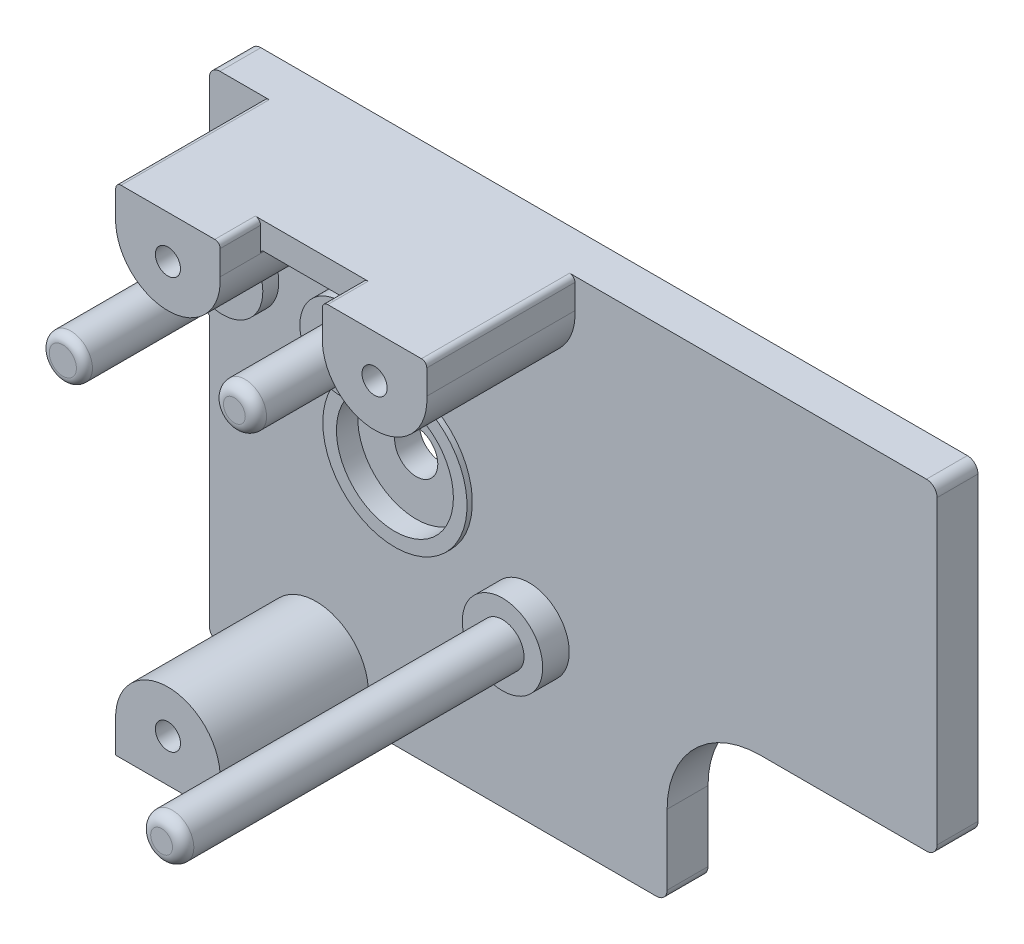
SolidWorks part; units mm, degrees
ref_plane "Alzado" through (0, 0, 0) normal (0, 0, 1) x (1, 0, 0)
ref_plane "Planta" through (0, 0, 0) normal (0, 1, 0) x (1, 0, 0)
ref_plane "Vista lateral" through (0, 0, 0) normal (1, 0, 0) x (0, 0, -1)
sketch "Croquis1" plane through (0, 0, 0) normal (0, 0, 1) x (1, 0, 0)
  line L0 (0, -55) -> (0, 55) construction
  line L1 (-68.325, 28.78) -> (68.325, 28.78)
  line L2 (-68.325, 28.78) -> (-68.325, 11.9)
  line L3 (-68.325, -64.4) -> (17.635, -64.4)
  line L4 (68.325, 28.78) -> (68.325, -31.7)
  line L5 (55, 0) -> (-55, 0) construction
  line L6 (17.635, -64.4) -> (17.635, -49.23)
  line L7 (35.165, -31.7) -> (68.325, -31.7)
  line L8 (-68.325, 0) -> (-104.5654, 0) construction
  line L9 (-73.325, 7.775) -> (-73.325, -7.775)
  line L10 (-73.325, 7.775) -> (-68.325, 11.9)
  line L11 (-73.325, -7.775) -> (-68.325, -11.9)
  line L12 (-68.325, -11.9) -> (-68.325, -64.4)
  arc A0 (17.635, -49.23) -> (35.165, -31.7) centre (35.165, -49.23) cw
  point P1 (-68.325, 11.9)
  point P4 (0, 28.78)
  point P5 (-68.325, 0)
  point P10 (17.635, -64.4)
  point P11 (68.325, -31.7)
  point P14 (34.845, -31.7)
  point P16 (17.635, -51.65)
  point P19 (-68.325, -11.9)
  point P23 (-73.325, 0)
  point P25 (-73.325, 0)
  dimension "D7" = 17.53
  dimension "D1" = 93.18
  dimension "D2" = 15.55
  dimension "D3" = 60.48
  dimension "D4" = 85.96
  dimension "D5" = 33.48
  dimension "D6" = 12.75
  dimension "D8" = 5
  dimension "D9" = 11.9
  dimension "D10" = 11.9
  dimension "D11" = 28.78
extrude "Saliente-Extruir1" add sketch "Croquis1" along normal mid plane 7.68
sketch "Croquis2" plane through (0, 0, 3.84) normal (0, 0, 1) x (1, 0, 0)
  line L0 (68.325, 28.78) -> (-68.325, 28.78) construction
  line L1 (-58.075, 28.78) -> (-58.075, 12.78) construction
  line L2 (-58.075, 12.78) -> (0.325, 12.78) construction
  line L3 (0.325, 12.78) -> (0.325, 28.78) construction
  line L4 (-58.075, 23.18) -> (0.325, 23.18) construction
  line L5 (-58.075, 23.18) -> (-58.075, 28.78)
  line L6 (-19.275, 28.78) -> (-19.275, 12.78) construction
  line L7 (-38.475, 28.78) -> (-38.475, 12.78) construction
  line L8 (-58.075, 28.78) -> (-38.475, 28.78)
  line L9 (-38.475, 28.78) -> (-38.475, 23.18)
  line L11 (-19.275, 23.18) -> (-19.275, 28.78)
  line L12 (-19.275, 28.78) -> (0.325, 28.78)
  line L13 (0.325, 28.78) -> (0.325, 23.18)
  arc A0 (-58.075, 23.18) -> (-38.475, 23.18) centre (-48.275, 22.5973) ccw
  arc A1 (-19.275, 23.18) -> (0.325, 23.18) centre (-9.475, 22.5973) ccw
  point P0 (0.325, 28.78)
  point P1 (-19.275, 28.78)
  point P5 (-38.475, 28.78)
  point P6 (-58.075, 28.78)
  point P15 (-38.475, 23.18)
  point P18 (-19.275, 23.18)
  point P19 (-58.075, 23.18)
  point P27 (-19.275, 23.18)
  dimension "D1" = 68
  dimension "D2" = 19.6
  dimension "D3" = 19.2
  dimension "D4" = 19.6
  dimension "D5" = 16
  dimension "D6" = 5.6
extrude "Saliente-Extruir2" add sketch "Croquis2" along normal blind 27.82
sketch "Croquis5" plane through (0, 0, 3.84) normal (0, 0, 1) x (1, 0, 0)
  line L0 (-38.475, 28.78) -> (-19.275, 28.78)
  line L1 (-19.275, 28.78) -> (-19.275, 23.82)
  line L2 (-19.275, 28.78) -> (-19.275, 23.18) construction
  line L3 (-19.275, 23.82) -> (-38.475, 23.82)
  line L4 (-38.475, 23.18) -> (-38.475, 28.78) construction
  line L5 (-38.475, 23.82) -> (-38.475, 28.78)
  dimension "D1" = 4.96
extrude "Saliente-Extruir3" add sketch "Croquis5" along normal blind 20.22
fillet "Redondeo1" radius 0.6 1 edges at (-38.475, 23.82, 13.95)
fillet "Redondeo4" radius 0.6 1 edges at (-19.275, 23.82, 13.95)
sketch "Croquis6" plane through (0, 0, 0) normal (0, 0, 1) x (1, 0, 0)
  line L0 (-38.475, 28.78) -> (-58.075, 28.78) construction
  line L1 (0.325, 28.78) -> (-19.275, 28.78) construction
  line L2 (-48.275, 28.78) -> (-48.275, 12.78) construction
  line L3 (-9.475, 28.78) -> (-9.475, 12.78) construction
  arc A0 (-58.075, 23.18) -> (-38.475, 23.18) centre (-48.275, 22.5973) ccw construction
  arc A1 (-19.275, 23.18) -> (0.325, 23.18) centre (-9.475, 22.5973) ccw construction
  circle A2 centre (-48.275, 20.78) radius 2.36
  circle A3 centre (-9.475, 20.78) radius 2.36
  point P0 (-48.275, 28.78)
  point P1 (-9.475, 28.78)
  point P16 (-48.275, 20.78)
  point P17 (-9.475, 20.78)
  dimension "D1" = 4.72
extrude "Cortar-Extruir1" cut sketch "Croquis6" against normal mid plane 107.9
sketch "Croquis9" plane through (0, 0, 3.84) normal (0, 0, 1) x (1, 0, 0)
  line L0 (-68.325, -64.4) -> (17.635, -64.4) construction
  line L2 (-58.075, -64.4) -> (-58.075, -48.4) construction
  line L3 (-58.075, -48.4) -> (-38.475, -48.4) construction
  line L4 (-38.475, -48.4) -> (-38.475, -64.4) construction
  line L5 (-58.075, -58.8) -> (-38.475, -58.8) construction
  line L6 (-58.075, -58.8) -> (-58.075, -64.4)
  line L7 (-58.075, -64.4) -> (-38.475, -64.4)
  line L8 (-38.475, -64.4) -> (-38.475, -58.8)
  line L9 (-58.075, 28.78) -> (-58.075, -64.4) construction
  arc A0 (-58.075, -58.8) -> (-38.475, -58.8) centre (-48.275, -58.2173) cw
  point P0 (-38.475, -64.4)
  point P5 (-58.075, -64.4)
  point P8 (-58.075, -58.8)
  dimension "D2" = 19.6
  dimension "D3" = 16
  dimension "D4" = 5.6
extrude "Saliente-Extruir6" add sketch "Croquis9" along normal blind 27.82
sketch "Croquis10" plane through (0, 0, 3.84) normal (0, 0, 1) x (1, 0, 0)
  line L0 (-58.075, 28.78) -> (-58.075, -64.4) construction
  line L1 (-58.075, -64.4) -> (-38.475, -64.4) construction
  line L2 (-48.275, -64.4) -> (-48.275, -48.4) construction
  arc A0 (-38.475, -58.8) -> (-58.075, -58.8) centre (-48.275, -58.2173) ccw construction
  circle A1 centre (-48.275, -56.4) radius 2.36
  point P5 (-48.275, -64.4)
  dimension "D1" = 4.72
extrude "Cortar-Extruir9" cut sketch "Croquis10" along normal blind 53 and the other way blind 66
fillet "Redondeo5" radius 5 1 edges at (-73.325, -7.775, 0)
fillet "Redondeo6" radius 5 1 edges at (-73.325, 7.775, 0)
sketch "Croquis12" plane through (0, 0, 3.84) normal (0, 0, 1) x (1, 0, 0)
  line L0 (-73.325, 5.4181) -> (-73.325, -5.4181) construction
  line L1 (19.525, 0) -> (-19.525, 0) construction
  line L2 (-62.825, 0) -> (-27.8016, 0) construction
  circle A0 centre (-62.825, 0) radius 4.05
  circle A1 centre (-38.625, 0) radius 4.05
  point P0 (-73.325, 0)
  point P1 (-62.825, 0)
  point P8 (-38.625, 0)
  dimension "D2" = 8.1
  dimension "D4" = 8.1
  dimension "D1" = 10.5
  dimension "D3" = 24.2
extrude "Cortar-Extruir10" cut sketch "Croquis12" against normal mid plane 30
fillet "Redondeo8" radius 2 1 edges at (-68.325, 28.78, 0)
fillet "Redondeo9" radius 1 2 edges
fillet "Redondeo10" radius 1 1 edges at (-19.275, 28.78, 27.86)
fillet "Redondeo12" radius 2 1 edges at (-68.325, -64.4, 0)
fillet "Redondeo13" radius 1 1 edges
fillet "Redondeo14" radius 1 1 edges at (0.325, 28.78, 17.75)
fillet "Redondeo15" radius 2 2 edges at (68.325, 28.78, 0)
fillet "Redondeo16" radius 2 1 edges at (68.325, -31.7, 0)
fillet "Redondeo17" radius 2 1 edges at (17.635, -64.4, 0)
fillet "Redondeo18" radius 1 1 edges at (-38.475, -64.4, 17.75)
sketch "Croquis14" plane through (0, 0, 3.84) normal (0, 0, 1) x (1, 0, 0)
  line L0 (-39.475, -64.4) -> (15.635, -64.4) construction
  line L1 (-32.475, -64.4) -> (-32.475, -4.174) construction
  circle A0 centre (-32.475, -17.65) radius 13.54
  point P0 (-39.475, -64.4)
  point P1 (-32.475, -64.4)
  point P7 (-32.475, -17.65)
  dimension "D1" = 7
  dimension "D2" = 46.75
extrude "Saliente-Extruir7" add sketch "Croquis14" along normal blind 1
sketch "Croquis15" plane through (0, 0, 4.84) normal (0, 0, 1) x (1, 0, 0)
  circle A0 centre (-32.475, -17.65) radius 10.98
  point P0 (-32.475, -17.65)
  dimension "D1" = 21.96
extrude "Cortar-Extruir12" cut sketch "Croquis15" against normal blind 4
sketch "Croquis16" plane through (0, 0, 0.84) normal (0, 0, 1) x (1, 0, 0)
  circle A0 centre (-32.475, -17.65) radius 4.05
  point P0 (-32.475, -17.65)
  dimension "D1" = 8.1
extrude "Cortar-Extruir13" cut sketch "Croquis16" against normal blind 24
sketch "Croquis17" plane through (0, 0, 3.84) normal (0, 0, 1) x (1, 0, 0)
  circle A0 centre (-62.825, 0) radius 7.545
  point P0 (-62.825, 0)
  dimension "D1" = 15.09
extrude "Saliente-Extruir8" add sketch "Croquis17" along normal blind 3
sketch "Croquis18" plane through (0, 0, 6.84) normal (0, 0, 1) x (1, 0, 0)
  circle A0 centre (-62.825, 0) radius 4.05
  point P0 (-62.825, 0)
sketch "Croquis20" plane through (0, 0, 3.84) normal (0, 0, 1) x (1, 0, 0)
  arc A0 (-32.1224, -4.1146) -> (-41.1626, -7.2646) centre (-38.625, 0) ccw
  arc A1 (-32.1224, -4.1146) -> (-41.1626, -7.2646) centre (-32.475, -17.65) ccw
  point P0 (-38.625, 0)
  point P4 (-32.475, -17.65)
  dimension "D1" = 15.39
extrude "Saliente-Extruir9" add sketch "Croquis20" along normal blind 5
sketch "Croquis22" plane through (0, 0, 4.84) normal (0, 0, 1) x (1, 0, 0)
  arc A0 (-41.1581, -7.2608) -> (-32.1283, -4.1144) centre (-38.625, 0) ccw
  arc A1 (-32.1283, -4.1144) -> (-41.1581, -7.2608) centre (-32.475, -17.65) ccw
  point P0 (-38.625, 0)
  dimension "D1" = 15.38
extrude "Saliente-Extruir10" add sketch "Croquis22" along normal blind 4
sketch "Croquis23" plane through (0, 0, 8.84) normal (0, 0, 1) x (1, 0, 0)
  circle A0 centre (-38.625, 0) radius 4.05
  point P0 (-38.625, 0)
extrude "Saliente-Extruir11" add sketch "Croquis23" along normal blind 20
extrude "Saliente-Extruir12" add sketch "Croquis18" along normal blind 30
fillet "Redondeo19" radius 1.5 1 edges at (-58.775, 0, 36.84)
fillet "Redondeo20" radius 2 1 edges at (-34.575, 0, 28.84)
sketch "Croquis24" plane through (0, 0, 3.84) normal (0, 0, 1) x (1, 0, 0)
  line L2 (17.635, -49.23) -> (-32.475, -17.65) construction
  arc A8 (-41.1626, -7.2646) -> (-32.1224, -4.1146) centre (-32.475, -17.65) ccw construction
  circle A9 centre (-8.2833, -32.8959) radius 7.545
  point P2 (-14.6665, -28.8732)
  point P3 (-21.02, -24.8691)
  point P10 (-8.2833, -32.8959)
  dimension "D1" = 7.51
  dimension "D2" = 7.545
extrude "Saliente-Extruir13" add sketch "Croquis24" along normal blind 5
sketch "Croquis25" plane through (0, 0, 8.84) normal (0, 0, 1) x (1, 0, 0)
  circle A0 centre (-8.2833, -32.8959) radius 4.05
  point P0 (-8.2833, -32.8959)
  dimension "D1" = 8.1
extrude "Saliente-Extruir14" add sketch "Croquis25" along normal blind 64
fillet "Redondeo21" radius 2 1 edges at (-4.2333, -32.8959, 72.84)
